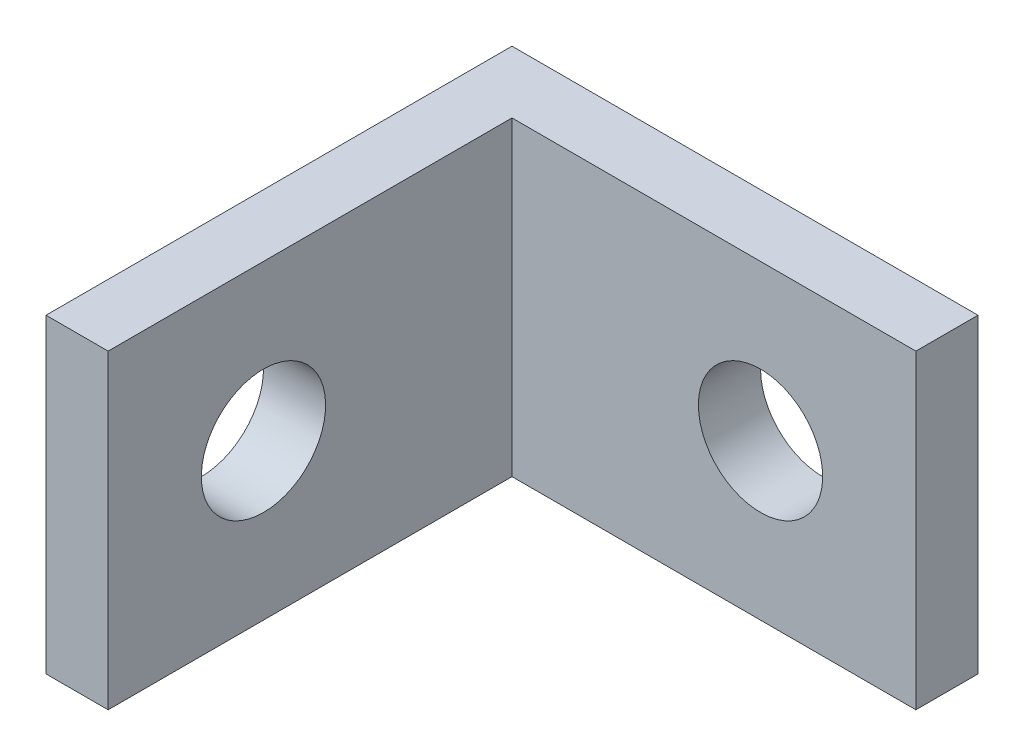
SolidWorks part; units mm, degrees
ref_plane "Front Plane" through (0, 0, 0) normal (0, 0, 1) x (1, 0, 0)
ref_plane "Top Plane" through (0, 0, 0) normal (0, 1, 0) x (1, 0, 0)
ref_plane "Right Plane" through (0, 0, 0) normal (1, 0, 0) x (0, 0, -1)
sketch "Sketch1" plane through (0, 0, 0) normal (0, 0, 1) x (1, 0, 0)
  line L1 (-7.5, 5) -> (7.5, 5)
  line L2 (-7.5, 5) -> (-7.5, -5)
  line L3 (-7.5, -5) -> (7.5, -5)
  line L4 (7.5, 5) -> (7.5, -5)
  line L5 (-7.5, 5) -> (7.5, -5) construction
  line L6 (-7.5, -5) -> (7.5, 5) construction
  point P0 (0, 0)
  dimension "D1" = 10
  dimension "D2" = 15
extrude "Boss-Extrude1" add sketch "Sketch1" along normal blind 2
sketch "Sketch2" plane through (0, 0, 2) normal (0, 0, 1) x (1, 0, 0)
  line L0 (-7.5, -5) -> (7.5, -5) construction
  line L1 (-7.5, 5) -> (-5.5, 5)
  line L2 (-7.5, 5) -> (-7.5, -5)
  line L3 (-7.5, -5) -> (-5.5, -5)
  line L4 (-5.5, 5) -> (-5.5, -5)
  dimension "D1" = 2
extrude "Boss-Extrude2" add sketch "Sketch2" along normal blind 13
sketch "Sketch3" plane through (0, 0, 0) normal (0, 0, -1) x (-1, 0, 0)
  line L0 (7.5, 5) -> (7.5, -5) construction
  circle A0 centre (-2.5, 0) radius 2
  dimension "D1" = 4
  dimension "D2" = 10
extrude "Cut-Extrude1" cut sketch "Sketch3" against normal blind 13
sketch "Sketch4" plane through (-7.5, 0, 0) normal (-1, 0, 0) x (0, 0, 1)
  line L0 (0, 5) -> (0, -5) construction
  line L2 (15, 5) -> (0, 5) construction
  circle A0 centre (10, 0) radius 2
  dimension "D1" = 4
  dimension "D2" = 10
  dimension "D3" = 5
extrude "Cut-Extrude2" cut sketch "Sketch4" against normal blind 13
